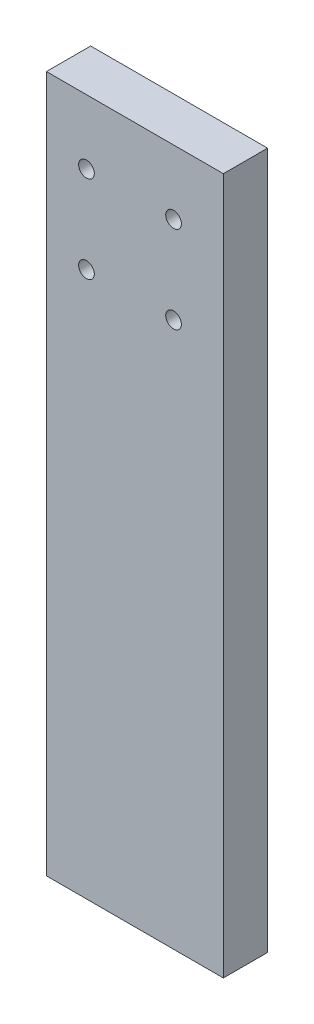
SolidWorks part; units mm, degrees
ref_plane "Alzado" through (0, 0, 0) normal (0, 0, 1) x (1, 0, 0)
ref_plane "Planta" through (0, 0, 0) normal (0, 1, 0) x (1, 0, 0)
ref_plane "Vista lateral" through (0, 0, 0) normal (1, 0, 0) x (0, 0, -1)
sketch "Croquis1" plane through (0, 0, 0) normal (0, 0, 1) x (1, 0, 0)
  line L1 (-24, 62) -> (26.8, 62)
  line L2 (-24, 62) -> (-24, -138)
  line L3 (-24, -138) -> (26.8, -138)
  line L4 (26.8, 62) -> (26.8, -138)
  circle A0 centre (-12.5, 18.5) radius 2.25 construction
  circle A1 centre (12.5, 18.5) radius 2.25 construction
  circle A2 centre (12.5, 43.5) radius 2.25 construction
  circle A3 centre (-12.5, 43.5) radius 2.25 construction
  circle A4 centre (-12.5, 18.5) radius 2.25
  circle A5 centre (12.5, 18.5) radius 2.25
  circle A6 centre (12.5, 43.5) radius 2.25
  circle A7 centre (-12.5, 43.5) radius 2.25
  dimension "D1" = 200
  dimension "D2" = 50.8
extrude "Saliente-Extruir1" add sketch "Croquis1" along normal blind 12.7 contours L4 L1 L2 L3 A7 A6 A5 A4
sketch "Croquis2" plane through (0, -138, 0) normal (0, -1, 0) x (1, 0, 0)
  line L0 (-24, 6.35) -> (26.8, 6.35) construction
  line L1 (-24, 12.7) -> (-24, 0) construction
  line L2 (26.8, 12.7) -> (26.8, 0) construction
  line L3 (1.4, 0) -> (1.4, 12.7) construction
  line L4 (-24, 12.7) -> (26.8, 12.7) construction
  circle A0 centre (-13.6, 6.35) radius 1.5
  circle A1 centre (16.4, 6.35) radius 1.5
  point P11 (1.4, 6.35)
  dimension "D1" = 3
  dimension "D2" = 3
  dimension "D3" = 15
  dimension "D4" = 15
extrude "Cortar-Extruir1" cut sketch "Croquis2" against normal blind 20
equation "\"D2@Croquis2\"=\"D1@Croquis2\""
equation "\"D4@Croquis2\"=\"D3@Croquis2\""
